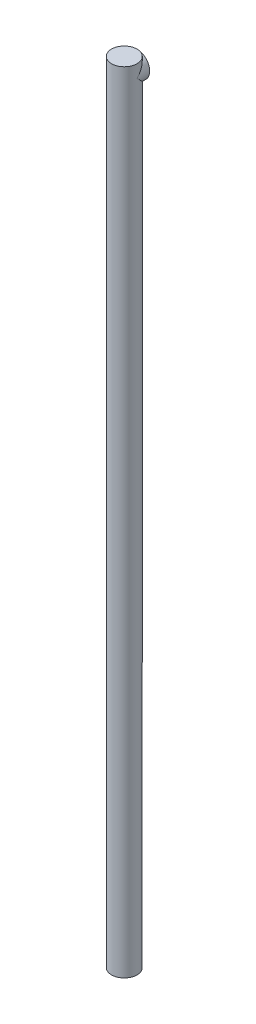
SolidWorks part; units mm, degrees
material "기본 (2)"
ref_plane "정면" through (0, 0, 0) normal (0, 0, 1) x (1, 0, 0)
ref_plane "윗면" through (0, 0, 0) normal (0, 1, 0) x (1, 0, 0)
ref_plane "우측면" through (0, 0, 0) normal (1, 0, 0) x (0, 0, -1)
sketch "스케치1" plane through (0, 0, 0) normal (0, 1, 0) x (1, 0, 0)
  circle A0 centre (0, 0) radius 2.5
extrude "보스-돌출1" add sketch "스케치1" along normal blind 155
sketch "스케치2" plane through (0, 0, 0) normal (0, 0, 1) x (1, 0, 0)
  line L0 (2.5, 155) -> (-2.5, 155) construction
  circle A0 centre (0, 152.5) radius 2.5
  dimension "D1" = 2.5
extrude "보스-돌출2" add sketch "스케치2" against normal blind 2.5
